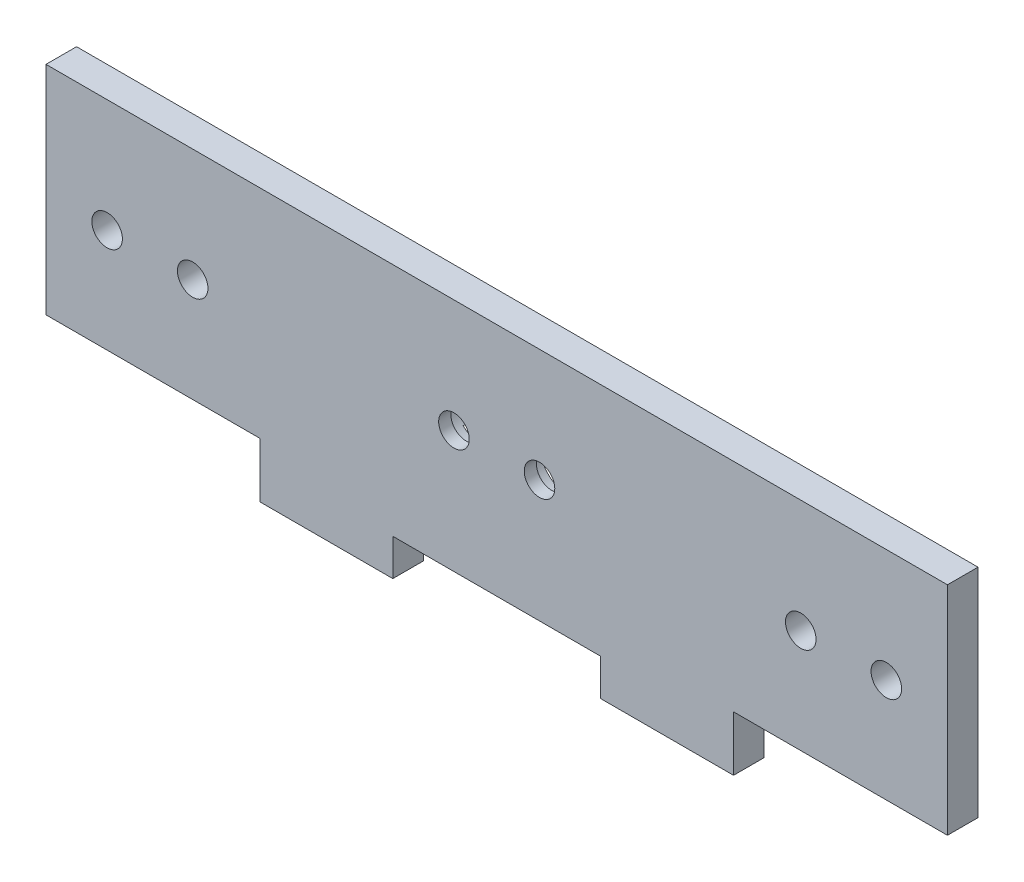
SolidWorks part; units mm, degrees
ref_plane "Front Plane" through (0, 0, 0) normal (0, 0, 1) x (1, 0, 0)
ref_plane "Top Plane" through (0, 0, 0) normal (0, 1, 0) x (1, 0, 0)
ref_plane "Right Plane" through (0, 0, 0) normal (1, 0, 0) x (0, 0, -1)
sketch "Sketch1" plane through (0, 0, 0) normal (0, 0, 1) x (1, 0, 0)
  line L1 (-73.75, 26.75) -> (73.75, 26.75)
  line L2 (-73.75, 26.75) -> (-73.75, -26.75)
  line L3 (-73.75, -26.75) -> (73.75, -26.75)
  line L4 (73.75, 26.75) -> (73.75, -26.75)
  line L5 (-73.75, 26.75) -> (73.75, -26.75) construction
  line L6 (-73.75, -26.75) -> (73.75, 26.75) construction
  point P0 (0, 0)
  dimension "D1" = 147.5
  dimension "D2" = 53.5
extrude "Boss-Extrude1" add sketch "Sketch1" along normal blind 5
sketch "Sketch2" plane through (0, 0, 0) normal (0, 0, -1) x (-1, 0, 0)
  line L0 (73.75, 26.75) -> (73.75, -26.75) construction
  line L1 (-73.75, 26.75) -> (73.75, 26.75) construction
  circle A0 centre (12.5, 9.25) radius 5
  circle A1 centre (-12.5, 9.25) radius 5
  dimension "D1" = 10
  dimension "D2" = 61.25
  dimension "D3" = 17.5
  dimension "D4" = 2
extrude "Boss-Extrude2" add sketch "Sketch2" along normal blind 7
sketch "Sketch3" plane through (0, 0, 5) normal (0, 0, 1) x (1, 0, 0)
  line L0 (0, 0) -> (0, 50.6331) construction
  line L1 (-73.75, -26.75) -> (-38.75, -26.75)
  line L2 (-73.75, -26.75) -> (-73.75, -8.75)
  line L3 (-73.75, -8.75) -> (-38.75, -8.75)
  line L4 (-38.75, -26.75) -> (-38.75, -8.75)
  line L5 (38.75, -26.75) -> (38.75, -8.75)
  line L6 (73.75, -8.75) -> (38.75, -8.75)
  line L7 (73.75, -26.75) -> (73.75, -8.75)
  line L8 (73.75, -26.75) -> (38.75, -26.75)
  dimension "D1" = 35
  dimension "D2" = 18
extrude "Cut-Extrude1" cut sketch "Sketch3" against normal through all
sketch "Sketch4" plane through (0, 0, 5) normal (0, 0, 1) x (1, 0, 0)
  line L8 (38.75, -8.75) -> (38.75, -26.75) construction
  line L9 (-17, -11.75) -> (17, -11.75)
  line L10 (-17, -11.75) -> (-17, -26.75)
  line L11 (-17, -26.75) -> (17, -26.75)
  line L12 (17, -11.75) -> (17, -26.75)
  line L13 (73.75, 26.75) -> (-73.75, 26.75) construction
  line L14 (-38.75, -26.75) -> (38.75, -26.75) construction
  line L15 (-38.75, -26.75) -> (-38.75, -8.75) construction
  dimension "D1" = 21.75
  dimension "D2" = 38.5
  dimension "D3" = 0
  dimension "D4" = 21.75
extrude "Cut-Extrude2" cut sketch "Sketch4" against normal blind 10
sketch "Sketch5" plane through (0, 0, 5) normal (0, 0, 1) x (1, 0, 0)
  line L3 (73.75, -8.75) -> (73.75, 26.75) construction
  line L4 (73.75, 26.75) -> (-73.75, 26.75) construction
  line L5 (0, -11.75) -> (0, 31.5901) construction
  line L6 (17, -11.75) -> (-17, -11.75) construction
  circle A2 centre (63.75, 8.25) radius 2.5
  circle A3 centre (49.75, 8.25) radius 2.5
  circle A4 centre (7, 8.25) radius 2.5
  circle A5 centre (-49.75, 8.25) radius 2.5
  circle A6 centre (-63.75, 8.25) radius 2.5
  circle A7 centre (-7, 8.25) radius 2.5
  dimension "D1" = 5
  dimension "D2" = 10
  dimension "D3" = 18.5
  dimension "D4" = 14
  dimension "D5" = 5
  dimension "D6" = 42.75
  dimension "D8" = 14
  dimension "D7" = 2
extrude "Cut-Extrude3" cut sketch "Sketch5" against normal through all
sketch "Sketch6" plane through (0, 0, -7) normal (0, 0, -1) x (-1, 0, 0)
  circle A0 centre (7, 8.25) radius 5
  circle A1 centre (-7, 8.25) radius 5
extrude "Cut-Extrude4" cut sketch "Sketch6" against normal blind 10
sketch "Sketch7" plane through (0, 0, 5) normal (0, 0, 1) x (1, 0, 0)
  line L0 (38.75, -8.75) -> (38.75, -26.75) construction
  line L1 (-38.75, -26.75) -> (38.75, -26.75)
  line L2 (-38.75, -26.75) -> (-38.75, -17.75)
  line L3 (-38.75, -17.75) -> (38.75, -17.75)
  line L4 (38.75, -26.75) -> (38.75, -17.75)
extrude "Cut-Extrude5" cut sketch "Sketch7" against normal blind 10
